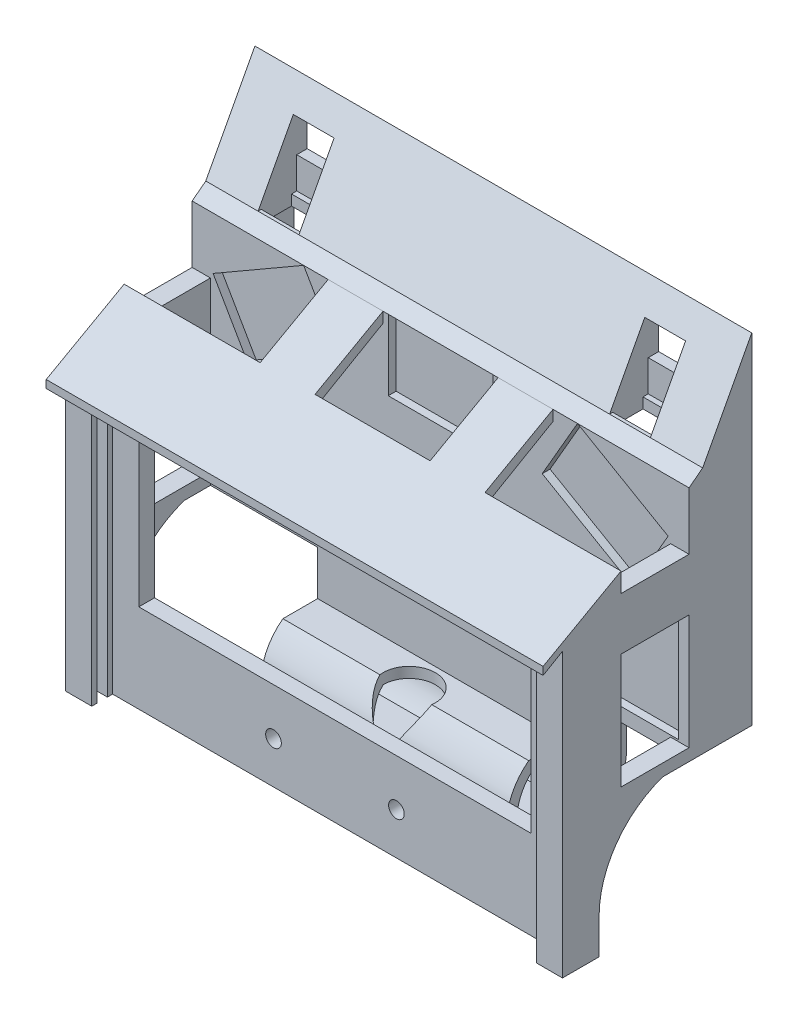
SolidWorks part; units mm, degrees
ref_plane "Alzado" through (0, 0, 0) normal (0, 0, 1) x (1, 0, 0)
ref_plane "Planta" through (0, 0, 0) normal (0, 1, 0) x (1, 0, 0)
ref_plane "Vista lateral" through (0, 0, 0) normal (1, 0, 0) x (0, 0, -1)
sketch "Croquis2" plane through (0, 0, 0) normal (0, 0, 1) x (1, 0, 0)
  line L0 (-47.5, -17.5) -> (-23.5, -17.5)
  line L1 (-47.5, 47.5) -> (47.5, 47.5)
  line L2 (-47.5, 47.5) -> (-47.5, -17.5)
  line L3 (-23.5, -47.5) -> (23.5, -47.5)
  line L4 (47.5, 47.5) -> (47.5, -17.5)
  line L5 (-47.5, 47.5) -> (23.5, -23.5) construction
  line L6 (-23.5, -23.5) -> (47.5, 47.5) construction
  line L7 (-23.5, -17.5) -> (-23.5, -47.5)
  line L8 (23.5, -47.5) -> (23.5, -17.5)
  line L9 (23.5, -17.5) -> (47.5, -17.5)
  point P0 (0, 0)
  dimension "D1" = 24
  dimension "D2" = 30
  dimension "D3" = 30
  dimension "D4" = 24
  dimension "D6" = 95
extrude "Saliente-Extruir1" add sketch "Croquis2" along normal blind 12
sketch "Croquis3" plane through (-47.5, 0, 0) normal (-1, 0, 0) x (0, 0, 1)
  line L1 (0, 47.5) -> (0, -17.5) construction
  line L3 (-1, 50.5) -> (-1, -3.4883) construction
  line L9 (0, 47.5) -> (9.3894, 29.841)
  line L10 (9.3894, 29.841) -> (12, 29.841)
  line L11 (12, 47.5) -> (12, -17.5) construction
  line L12 (12, 29.841) -> (12, 47.5)
  line L13 (12, 47.5) -> (0, 47.5)
  dimension "D1" = 28
  dimension "D2" = 20
  dimension "D3" = 1
extrude "Cortar-Extruir1" cut sketch "Croquis3" against normal through all
sketch "Croquis4" plane through (-47.5, 0, 0) normal (-1, 0, 0) x (0, 0, 1)
  line L2 (39.9, 13.733) -> (39.9, 10.733)
  line L5 (-2, -18.4986) -> (-2, -43.5945) construction
  line L6 (0, -17.5) -> (0, -47.5) construction
  line L9 (12, -17.5) -> (17, -17.5)
  line L10 (32.1961, -33.2172) -> (32.1961, 15.1808)
  line L11 (39.9, 10.733) -> (32.1961, 15.1808)
  line L12 (32.1961, -33.2172) -> (32.1961, -41.2172)
  line L13 (29.1961, -34.5) -> (29.1961, -41.2172)
  line L14 (29.1961, -41.2172) -> (32.1961, -41.2172)
  line L15 (12, -17.5) -> (12, 29.841)
  line L16 (12, 29.841) -> (39.9, 13.733)
  circle A0 centre (11.25, -34.5) radius 13.25 construction
  arc A2 (29.1961, -34.5) -> (17, -17.5) centre (11.25, -34.5) ccw
  dimension "D6" = 26.5
  dimension "D2" = 3
  dimension "D3" = 60
  dimension "D4" = 2
  dimension "D5" = 17
  dimension "D7" = 5
  dimension "D8" = 3
  dimension "D9" = 27.9
  dimension "D10" = 48.398
  dimension "D11" = 8
  dimension "D12" = 60
extrude "Saliente-Extruir2" add sketch "Croquis4" against normal through all
ref_plane "Plano1" through (0, 0, 0) normal (-1, 0, 0) x (0, 0, 1)
sketch "Croquis5" plane through (0, 0, 0) normal (-1, 0, 0) x (0, 0, 1)
  line L0 (12, -17.5) -> (12, 29.841) construction
  line L1 (17, -17.5) -> (0, -17.5) construction
  line L2 (12, 25.841) -> (29.1961, 15.9129)
  line L3 (32.1961, -41.2172) -> (32.1961, 15.1808) construction
  line L4 (29.1961, 15.9129) -> (29.1961, -32.0871)
  line L6 (12, -17.5) -> (12, 25.841)
  line L7 (29.1961, -32.0871) -> (12, -32.0871)
  line L8 (12, -17.5) -> (12, -47.5) construction
  line L9 (12, -32.0871) -> (12, -17.5)
  dimension "D1" = 4
  dimension "D2" = 60
  dimension "D3" = 3
  dimension "D4" = 48
extrude "Cortar-Extruir2" cut sketch "Croquis5" against normal blind 44 and the other way blind 44
sketch "Croquis6" plane through (0, 0, 32.1961) normal (0, 0, 1) x (1, 0, 0)
  line L0 (47.5, 10.733) -> (-47.5, 10.733) construction
  line L1 (-37.5, 10.733) -> (37.5, 10.733)
  line L2 (-37.5, 10.733) -> (-37.5, -24.267)
  line L3 (-37.5, -24.267) -> (37.5, -24.267)
  line L4 (37.5, 10.733) -> (37.5, -24.267)
  line L5 (47.5, -41.2172) -> (47.5, 15.1808) construction
  dimension "D1" = 75
  dimension "D2" = 35
  dimension "D3" = 0
  dimension "D4" = 10
extrude "Cortar-Extruir3" cut sketch "Croquis6" against normal blind 5
sketch "Croquis7" plane through (0, 0, 12) normal (0, 0, 1) x (1, 0, 0)
  line L0 (0, 21.945) -> (0, -21.945) construction
  line L1 (-10, 27.841) -> (10, 27.841)
  line L2 (-10, 27.841) -> (-10, 14.341)
  line L3 (-10, 14.341) -> (10, 14.341)
  line L4 (10, 27.841) -> (10, 14.341)
  line L5 (47.5, -41.2172) -> (47.5, 15.1808) construction
  line L6 (47.5, 29.841) -> (-47.5, 29.841) construction
  line L15 (26.1795, 27.841) -> (43.5, 17.841)
  line L16 (-47.5, 8.823) -> (47.5, 8.823) construction
  line L17 (-26.1795, 27.841) -> (-43.5, 17.841)
  line L18 (-26.1795, 27.841) -> (-19.4295, 16.1497)
  line L19 (-43.5, 17.841) -> (-36.75, 6.1497)
  line L20 (-19.4295, 16.1497) -> (-36.75, 6.1497)
  line L21 (26.1795, 27.841) -> (19.4295, 16.1497)
  line L22 (43.5, 17.841) -> (36.75, 6.1497)
  line L23 (19.4295, 16.1497) -> (36.75, 6.1497)
  line L25 (-47.5, -41.2172) -> (-47.5, 15.1808) construction
  line L26 (-45.5, 5.1497) -> (-32, 5.1497)
  line L27 (-45.5, 5.1497) -> (-45.5, -14.8503)
  line L28 (-45.5, -14.8503) -> (-32, -14.8503)
  line L29 (-32, 5.1497) -> (-32, -14.8503)
  line L30 (32, 5.1497) -> (45.5, 5.1497)
  line L31 (32, 5.1497) -> (32, -14.8503)
  line L32 (32, -14.8503) -> (45.5, -14.8503)
  line L33 (45.5, 5.1497) -> (45.5, -14.8503)
  line L35 (-47.5, 27.841) -> (47.5, 27.841) construction
  line L36 (-47.5, 13.733) -> (-47.5, 29.841) construction
  line L37 (47.5, 13.733) -> (47.5, 29.841) construction
  dimension "D1" = 20
  dimension "D2" = 13.5
  dimension "D3" = 10
  dimension "D4" = 2
  dimension "D6" = 20
  dimension "D8" = 13.5
  dimension "D9" = 30
  dimension "D10" = 30
  dimension "D11" = 13.5
  dimension "D12" = 4
  dimension "D13" = 1
  dimension "D14" = 13.5
  dimension "D15" = 20
  dimension "D16" = 20
  dimension "D17" = 13.5
  dimension "D18" = 2
  dimension "D19" = 4
  dimension "D20" = 1
  dimension "D21" = 20
  dimension "D22" = 2
sketch "Croquis8" plane through (47.5, 0, 0) normal (1, 0, 0) x (0, 0, -1)
  line L6 (-12, -14.1927) -> (-12, -15.1927) construction
  line L7 (-12, 5.1497) -> (-12, -14.8503) construction
  line L8 (-12, 5.1497) -> (-12, -14.8503) construction
  line L10 (-12, -15.1927) -> (-25, -15.1927)
  line L11 (-12, -15.1927) -> (-12, 6.8073)
  line L12 (-12, 6.8073) -> (-25, 6.8073)
  line L13 (-25, -15.1927) -> (-25, 6.8073)
  dimension "D1" = 1
  dimension "D2" = 22
  dimension "D3" = 13
extrude "Cortar-Extruir10" cut sketch "Croquis8" against normal through all
sketch "Croquis9" plane through (0, -47.5, 0) normal (0, -1, 0) x (1, 0, 0)
  line L0 (-10, 12) -> (-11, 12) construction
  line L2 (-11, 12) -> (11, 12)
  line L3 (-11, 12) -> (-11, 25)
  line L4 (-10, 12) -> (10, 12) construction
  line L5 (-10, 12) -> (10, 12) construction
  line L6 (0, 21.945) -> (0, -21.945) construction
  line L7 (-11, 25) -> (11, 25)
  line L8 (11, 12) -> (11, 25)
  dimension "D1" = 0
  dimension "D2" = 22
  dimension "D3" = 13
  dimension "D4" = 11
extrude "Cortar-Extruir11" cut sketch "Croquis9" against normal through all
sketch "Croquis10" plane through (-47.5, 0, 0) normal (-1, 0, 0) x (0, 0, 1)
  line L1 (12, 29.841) -> (25, 29.841)
  line L2 (12, 29.841) -> (12, 16.841)
  line L3 (12, 16.841) -> (25, 16.841)
  line L4 (25, 29.841) -> (25, 16.841)
  dimension "D1" = 13
  dimension "D2" = 13
  dimension "D3" = 0
extrude "Cortar-Extruir12" cut sketch "Croquis10" against normal blind 26
sketch "Croquis11" plane through (47.5, 0, 0) normal (1, 0, 0) x (0, 0, -1)
  line L1 (-12, 29.841) -> (-25, 29.841)
  line L2 (-12, 29.841) -> (-12, 16.841)
  line L3 (-12, 16.841) -> (-25, 16.841)
  line L4 (-25, 29.841) -> (-25, 16.841)
  dimension "D1" = 13
  dimension "D2" = 13
  dimension "D3" = 0
extrude "Cortar-Extruir13" cut sketch "Croquis11" against normal blind 26
sketch "Croquis12" plane through (0, 0, 0) normal (0, 0, -1) x (-1, 0, 0)
  line L1 (-40, -12.5) -> (40, -12.5)
  line L2 (-40, -12.5) -> (-40, 27.5)
  line L3 (-40, 27.5) -> (40, 27.5)
  line L4 (40, -12.5) -> (40, 27.5)
  dimension "D1" = 80
  dimension "D2" = 40
  dimension "D3" = 20
  dimension "D4" = 40
extrude "Cortar-Extruir15" cut sketch "Croquis12" against normal blind 6.3
sketch "Croquis14" plane through (-23.5, 0, 0) normal (-1, 0, 0) x (0, 0, 1)
  line L0 (-3, 17.3569) -> (-3, -48.8968) construction
  line L1 (0, -17.5) -> (0, -47.5) construction
  line L2 (17, -17.5) -> (0, -17.5) construction
  line L3 (17.75, -28.5) -> (6.75, -28.5) construction
  line L4 (6.75, -40.5) -> (17.75, -40.5) construction
  line L5 (6.5588, -41) -> (17.9412, -41)
  line L6 (17.9412, -28) -> (6.5588, -28)
  line L9 (5.851, -43) -> (18.649, -43)
  line L10 (18.649, -26) -> (5.851, -26)
  line L11 (1.6106, -34.5) -> (1.6106, -47.5) construction
  line L12 (12, -47.5) -> (0, -47.5) construction
  line L13 (3.6106, -34.5) -> (3.6106, -47.5) construction
  circle A0 centre (10.25, -34.5) radius 13.25 construction
  arc A1 (6.75, -28.5) -> (6.75, -40.5) centre (12.25, -34.5) ccw construction
  arc A2 (17.75, -40.5) -> (17.75, -28.5) centre (12.25, -34.5) ccw construction
  arc A3 (17.9412, -41) -> (17.9412, -28) centre (12.25, -34.5) ccw
  arc A4 (6.5588, -28) -> (6.5588, -41) centre (12.25, -34.5) ccw
  arc A7 (18.649, -43) -> (18.649, -26) centre (12.25, -34.5) ccw
  arc A8 (5.851, -26) -> (5.851, -43) centre (12.25, -34.5) ccw
  dimension "D2" = 26.5
  dimension "D1" = 3
  dimension "D3" = 17
  dimension "D4" = 11
  dimension "D5" = 11
  dimension "D6" = 12
  dimension "D7" = 6
  dimension "D8" = 7.5
  dimension "D9" = 0.5
  dimension "D10" = 2
extrude "Saliente-Extruir3" add sketch "Croquis14" against normal up to vertex
sketch "Croquis15" plane through (-23.5, 0, 0) normal (-1, 0, 0) x (0, 0, 1)
  line L0 (-1, -10.411) -> (-1, -48.0499) construction
  line L1 (0, -17.5) -> (0, -47.5) construction
  line L3 (17, -17.5) -> (0, -17.5) construction
  line L4 (12, -28) -> (6.9653, -28)
  line L5 (12, -41) -> (6.9653, -41)
  line L6 (20.3671, -27) -> (6.5636, -27) construction
  line L7 (4.273, -34.5) -> (0, -34.5) construction
  line L9 (20.3671, -42) -> (6.5636, -42) construction
  line L13 (12, -43) -> (12, -47.5)
  line L15 (12, -47.5) -> (0, -47.5)
  line L16 (12, -28) -> (12, -41)
  line L17 (19.9653, -28) -> (6.9653, -28) construction
  line L18 (19.9653, -41) -> (6.9653, -41) construction
  line L19 (20.3671, -42) -> (6.5636, -42) construction
  line L20 (0, -47.5) -> (0, -34.5)
  line L21 (12, -43) -> (5.9653, -43)
  circle A0 centre (12, -34.5) radius 13 construction
  arc A1 (6.9653, -28) -> (6.9653, -41) centre (13.4653, -34.5) ccw
  arc A3 (6.5636, -27) -> (6.5636, -42) centre (13.4653, -34.5) ccw construction
  arc A4 (20.3671, -42) -> (20.3671, -27) centre (13.4653, -34.5) ccw construction
  arc A6 (19.9653, -41) -> (19.9653, -28) centre (13.4653, -34.5) ccw construction
  spline S0 degree 2 poles (5.9653, -43) (0.6869, -40.7073) (0, -34.5) knots 0 0 0 1 1 1
  dimension "D2" = 26
  dimension "D1" = 1
  dimension "D3" = 17
  dimension "D4" = 1
  dimension "D7" = 1
sketch "Croquis16" plane through (0, -26, 0) normal (0, 1, 0) x (1, 0, 0)
  line L0 (0, 21.945) -> (0, -21.945) construction
  line L1 (23.5, -12) -> (-23.5, -12) construction
  circle A0 centre (0, -18) radius 5
  dimension "D1" = 10
  dimension "D2" = 6
extrude "Cortar-Extruir21" cut sketch "Croquis15" against normal up to surface (47 mm away) up to face at (23.5, -33.5, 11.1923)
extrude "Cortar-Extruir22" cut sketch "Croquis7" against normal blind 1.5
extrude "Cortar-Extruir17" cut sketch "Croquis16" against normal blind 10
sketch "Croquis19" plane through (0, 0, 32.1961) normal (0, 0, 1) x (1, 0, 0)
  line L0 (-23.5, -17.5) -> (-23.5, -26) construction
  line L1 (23.5, -26) -> (23.5, -17.5) construction
  line L2 (47.5, -41.2172) -> (-47.5, -41.2172) construction
  circle A0 centre (-11.75, -33.2172) radius 1.5
  circle A1 centre (11.75, -33.2172) radius 1.5
  dimension "D1" = 3
  dimension "D2" = 3
  dimension "D3" = 47
  dimension "D4" = 11.75
  dimension "D5" = 11.75
  dimension "D6" = 8
  dimension "D7" = 8
extrude "Cortar-Extruir18" cut sketch "Croquis19" against normal blind 10
sketch "Croquis21" plane through (0, 0, 0) normal (0, 0, -1) x (-1, 0, 0)
  line L1 (-37.5, 42.5) -> (-29.7, 42.5)
  line L2 (-37.5, 42.5) -> (-37.5, 29.5)
  line L3 (-37.5, 29.5) -> (-29.7, 29.5)
  line L4 (-29.7, 42.5) -> (-29.7, 29.5)
  line L5 (29.7, 42.5) -> (37.5, 42.5)
  line L6 (29.7, 42.5) -> (29.7, 29.5)
  line L7 (29.7, 29.5) -> (37.5, 29.5)
  line L8 (37.5, 42.5) -> (37.5, 29.5)
  line L9 (47.5, 47.5) -> (47.5, -17.5) construction
  line L10 (-47.5, -17.5) -> (-47.5, 47.5) construction
  line L11 (-47.5, 47.5) -> (47.5, 47.5) construction
  dimension "D1" = 7.8
  dimension "D2" = 13
  dimension "D3" = 7.8
  dimension "D4" = 13
  dimension "D5" = 5
  dimension "D6" = 5
  dimension "D7" = 10
  dimension "D8" = 10
extrude "Cortar-Extruir19" cut sketch "Croquis21" against normal blind 10
sketch "Croquis22" plane through (0, 0, 0) normal (-1, 0, 0) x (0, 0, 1)
  line L2 (7.3894, 29.9844) -> (7.3894, 4.0052) construction
  line L3 (39.9, 13.733) -> (39.9, 12.233)
  line L5 (39.9, 10.733) -> (39.9, 13.733) construction
  line L10 (39.9, 13.733) -> (12, 29.841)
  line L12 (39.9, 12.233) -> (12, 27.841)
  line L13 (12, 29.841) -> (12, 25.841) construction
  line L16 (12, 29.841) -> (12, 29.341)
  line L17 (12, 29.841) -> (12, 16.841) construction
  line L18 (12, 29.341) -> (9, 29.341)
  line L19 (9, 29.341) -> (9, 28.341)
  line L20 (9, 28.341) -> (12, 28.341)
  line L21 (12, 28.341) -> (12, 27.841)
  dimension "D1" = 2
  dimension "D2" = 1.5
  dimension "D3" = 60.776
  dimension "D4" = 0.5
  dimension "D5" = 0.5
  dimension "D6" = 3
extrude "Cortar-Extruir20" cut sketch "Croquis22" against normal up to surface and the other way up to surface
ref_plane "Plano2" through (-16, 0, 0) normal (-1, 0, 0) x (0, 0, 1)
sketch "Croquis23" plane through (0, 0, 0) normal (0, 0, -1) x (-1, 0, 0)
  line L10 (37.5, 29.5) -> (37.5, 42.5) construction
  line L11 (29.7, 29.5) -> (37.5, 29.5)
  line L12 (29.7, 29.5) -> (29.7, 35.5)
  line L13 (29.7, 35.5) -> (37.5, 35.5)
  line L14 (37.5, 29.5) -> (37.5, 35.5)
  line L15 (-29.7, 29.5) -> (-29.7, 42.5) construction
  line L16 (-37.5, 29.5) -> (-29.7, 29.5)
  line L17 (-37.5, 29.5) -> (-37.5, 35.5)
  line L18 (-37.5, 35.5) -> (-29.7, 35.5)
  line L19 (-29.7, 29.5) -> (-29.7, 35.5)
  dimension "D1" = 6
  dimension "D2" = 6
extrude "Saliente-Extruir4" add sketch "Croquis23" against normal blind 2
sketch "Croquis24" plane through (0, 29.5, 0) normal (0, 1, 0) x (1, 0, 0)
  line L0 (29.7, -9.3894) -> (29.7, -2.6585) construction
  line L1 (37.5, -10) -> (29.7, -10)
  line L2 (37.5, -10) -> (37.5, -3)
  line L3 (37.5, -3) -> (29.7, -3)
  line L4 (29.7, -10) -> (29.7, -3)
  line L5 (37.5, -2.6585) -> (37.5, -9.3894) construction
  line L9 (47.5, 0) -> (-47.5, 0) construction
  line L13 (0, 21.945) -> (0, -21.945) construction
  line L14 (-37.5, -3) -> (-29.7, -3)
  line L15 (-29.7, -10) -> (-29.7, -3)
  line L16 (-37.5, -10) -> (-29.7, -10)
  line L17 (-37.5, -10) -> (-37.5, -3)
  dimension "D1" = 0
  dimension "D2" = 3
  dimension "D3" = 7
  dimension "D4" = 0
  dimension "D5" = 7.8
extrude "Cortar-Extruir23" cut sketch "Croquis24" against normal blind 40 contours L1 L4 L3 L2 | L14 L15 L16 L17
sketch "Croquis25" plane through (0, 0, 6.3) normal (0, 0, -1) x (-1, 0, 0)
  line L1 (-29.7, -10.5) -> (-19.7, -10.5)
  line L2 (-29.7, -10.5) -> (-29.7, -0.5)
  line L3 (-29.7, -0.5) -> (-19.7, -0.5)
  line L4 (-19.7, -10.5) -> (-19.7, -0.5)
  line L5 (0, -21.945) -> (0, 21.945) construction
  line L6 (29.7, -0.5) -> (19.7, -0.5)
  line L7 (19.7, -10.5) -> (19.7, -0.5)
  line L8 (29.7, -10.5) -> (19.7, -10.5)
  line L9 (29.7, -10.5) -> (29.7, -0.5)
  dimension "D1" = 10
  dimension "D2" = 10
extrude "Cortar-Extruir24" cut sketch "Croquis25" against normal blind 2
sketch "Croquis26" plane through (0, 0, 6.3) normal (0, 0, -1) x (-1, 0, 0)
  line L1 (-29.7, -0.5) -> (-19.7, -0.5)
  line L2 (-29.7, -0.5) -> (-29.7, -10.5)
  line L3 (-29.7, -10.5) -> (-19.7, -10.5)
  line L4 (-19.7, -0.5) -> (-19.7, -10.5)
  line L5 (19.7, -10.5) -> (29.7, -10.5)
  line L6 (19.7, -10.5) -> (19.7, -0.5)
  line L7 (19.7, -0.5) -> (29.7, -0.5)
  line L8 (29.7, -10.5) -> (29.7, -0.5)
extrude "Cortar-Extruir27" cut sketch "Croquis26" against normal blind 10
sketch "Croquis28" plane through (0, 0, 0) normal (1, 0, 0) x (0, 0, -1)
  line L0 (-12, 27.841) -> (-9.3894, 29.841)
  line L1 (-9.3894, 29.841) -> (-8.7842, 29.841)
  line L2 (-8.7842, 29.841) -> (-8.7842, 27.841)
  line L3 (-8.7842, 27.841) -> (-12, 27.841)
  point P4 (-8.7853, 27.9269)
extrude "Saliente-Extruir5" add sketch "Croquis28" along normal mid plane 95
sketch "Croquis29" plane through (0, 0, 0) normal (1, 0, 0) x (0, 0, -1)
  line L0 (-12, 29.841) -> (-10, 29.841)
  line L2 (-10.0421, 29.341) -> (-11.3474, 28.341)
  line L5 (-12, 27.841) -> (-11.3474, 28.341)
  line L6 (-12, 29.841) -> (-12, 27.841)
  line L7 (-9.3894, 29.841) -> (-10.0421, 29.341)
  line L8 (-10, 29.841) -> (-9.3894, 29.841)
extrude "Cortar-Extruir28" cut sketch "Croquis29" against normal mid plane 95
sketch "Croquis32" plane through (0, 0, 29.1961) normal (0, 0, -1) x (-1, 0, 0)
  line L0 (-23.5, -34.5) -> (23.5, -34.5) construction
  line L1 (-19.6519, -34.5) -> (-14.6519, -34.5)
  line L2 (-19.6519, -34.5) -> (-19.6519, -41.22)
  line L3 (-19.6519, -41.22) -> (-14.6519, -41.22)
  line L4 (-14.6519, -34.5) -> (-14.6519, -41.22)
  line L5 (-47.5, -41.2172) -> (47.5, -41.2172) construction
  line L6 (-3.4226, -34.5) -> (1.5774, -34.5)
  line L7 (-3.4226, -34.5) -> (-3.4226, -41.2172)
  line L8 (-3.4226, -41.2172) -> (1.5774, -41.2172)
  line L9 (1.5774, -34.5) -> (1.5774, -41.2172)
  line L10 (14.8443, -34.5) -> (19.8443, -34.5)
  line L11 (14.8443, -34.5) -> (14.8443, -41.2172)
  line L12 (14.8443, -41.2172) -> (19.8443, -41.2172)
  line L13 (19.8443, -34.5) -> (19.8443, -41.2172)
  point P16 (14.8443, -41.2172)
  point P18 (-3.4226, -41.2172)
  dimension "D1" = 6.7172
  dimension "D2" = 5
  dimension "D3" = 6.72
  dimension "D4" = 5
  dimension "D5" = 5
extrude "Saliente-Extruir10" add sketch "Croquis32" along normal blind 8
sketch "Croquis34" plane through (-19.8443, 0, 0) normal (-1, 0, 0) x (0, 0, 1)
  line L0 (21.1961, -41.2172) -> (20.0446, -41.7417)
  line L1 (20.0446, -41.7417) -> (21.1961, -40.2588)
  line L6 (21.1961, -40.2588) -> (21.1961, -41.2172)
  line L7 (21.1961, -41.2172) -> (29.1961, -41.2172)
  line L8 (29.1961, -41.2172) -> (29.1961, -34.5)
  line L9 (29.1961, -34.5) -> (22.8894, -34.5)
  line L11 (21.1961, -41.2172) -> (29.1961, -41.2172)
  line L12 (29.1961, -41.2172) -> (29.1961, -34.5)
  line L13 (29.1961, -34.5) -> (22.8894, -34.5)
  arc A0 (18.649, -43) -> (18.649, -26) centre (12.25, -34.5) ccw construction
  arc A2 (21.1961, -40.2588) -> (22.8894, -34.5) centre (12.25, -34.5) ccw
  arc A3 (21.1961, -40.2588) -> (22.8894, -34.5) centre (12.25, -34.5) ccw
  point P3 (20.0446, -41.7417)
  dimension "D1" = 0
extrude "Saliente-Extruir11" add sketch "Croquis34" against normal blind 5
sketch "Croquis35" plane through (-1.5774, 0, 0) normal (-1, 0, 0) x (0, 0, 1)
  line L0 (21.1961, -41.2172) -> (20.0446, -41.7417)
  line L1 (20.0446, -41.7417) -> (21.1961, -41.2172) construction
  line L2 (20.0446, -41.7417) -> (21.1961, -40.2588)
  line L3 (21.1961, -41.2172) -> (21.1961, -40.2588) construction
  line L4 (21.1961, -40.2588) -> (21.1961, -41.2172)
extrude "Saliente-Extruir12" add sketch "Croquis35" against normal blind 5
sketch "Croquis36" plane through (14.6519, 0, 0) normal (-1, 0, 0) x (0, 0, 1)
  line L8 (21.1961, -40.2588) -> (21.1961, -41.22)
  line L9 (21.1961, -41.22) -> (29.1961, -41.22)
  line L10 (29.1961, -41.22) -> (29.1961, -41.2172)
  line L11 (29.1961, -41.2172) -> (29.1961, -34.5)
  line L12 (29.1961, -34.5) -> (22.8894, -34.5)
  line L15 (29.1961, -41.22) -> (29.1961, -41.2172)
  arc A2 (21.1961, -40.2588) -> (22.8894, -34.5) centre (12.25, -34.5) ccw
  point P0 (21.1961, -40.2588)
  dimension "D1" = 0
sketch "Croquis37" plane through (19.6519, 0, 0) normal (1, 0, 0) x (0, 0, -1)
  line L0 (-21.1961, -41.22) -> (-20.0446, -41.7417)
  line L1 (-20.0446, -41.7417) -> (-21.2044, -40.246)
  line L2 (-21.2044, -40.246) -> (-21.1961, -41.22)
  arc A0 (-18.649, -26) -> (-18.649, -43) centre (-12.25, -34.5) ccw construction
extrude "Saliente-Extruir13" add sketch "Croquis37" against normal blind 5
sketch "Croquis38" plane through (0, -41.2172, 0) normal (0, -1, 0) x (1, 0, 0)
  line L0 (-47.5, 32.1961) -> (-47.5, 36.1961)
  line L1 (-47.5, 32.1961) -> (-47.5, 39.9) construction
  line L2 (-47.5, 36.1961) -> (-42.5, 36.1961)
  line L3 (-42.5, 36.1961) -> (-42.5, 35.1961)
  line L4 (-42.5, 35.1961) -> (-46, 35.1961)
  line L5 (-46, 35.1961) -> (-46, 33.1961)
  line L6 (-46, 33.1961) -> (-42.5, 33.1961)
  line L7 (-42.5, 33.1961) -> (-42.5, 32.1961)
  line L8 (47.5, 32.1961) -> (-47.5, 32.1961) construction
  line L9 (-42.5, 32.1961) -> (-47.5, 32.1961)
  dimension "D1" = 2
  dimension "D2" = 1
  dimension "D3" = 1
  dimension "D4" = 5
  dimension "D5" = 5
  dimension "D6" = 1.5
extrude "Saliente-Extruir14" add sketch "Croquis38" against normal up to next
mirror "Simetría1" about plane through (0, 0, 0) normal (1, 0, 0) of "Saliente-Extruir14"
ref_plane "Plano4" through (0, -27.2172, 0) normal (0, -1, 0) x (-1, 0, 0)
